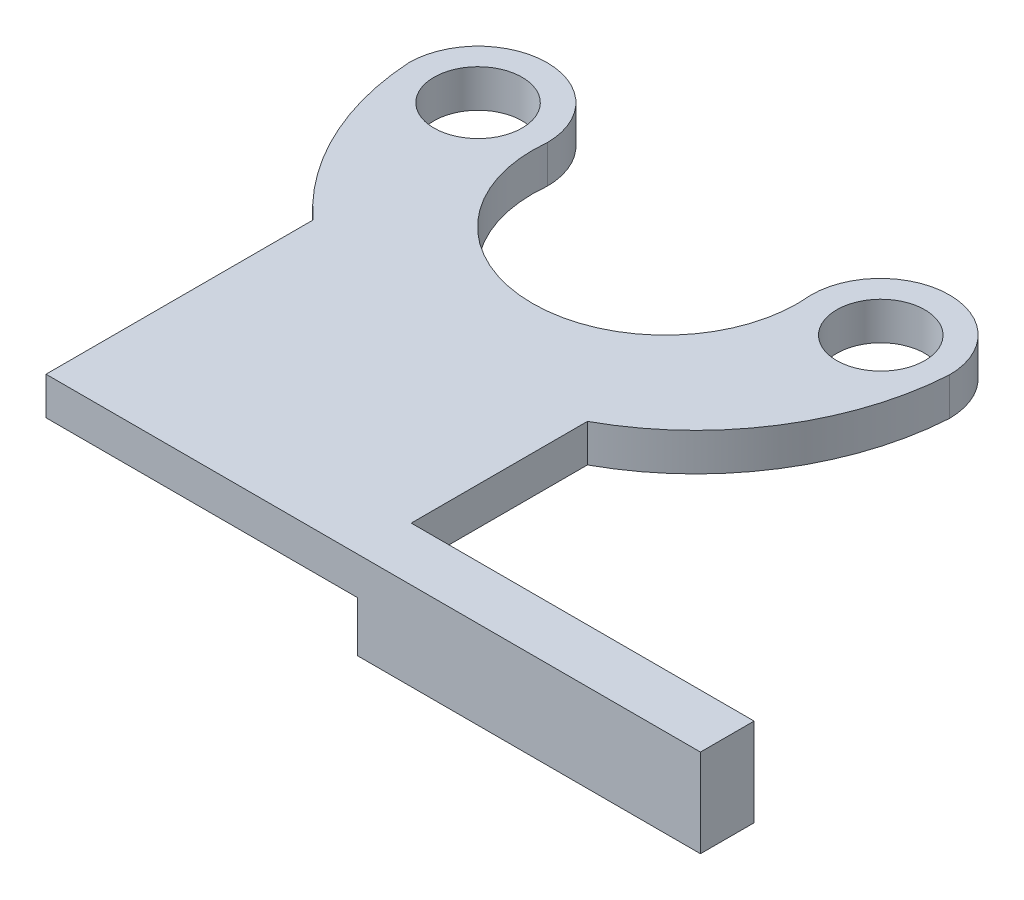
SolidWorks part; units mm, degrees
ref_plane "前视基准面" through (0, 0, 0) normal (0, 0, 1) x (1, 0, 0)
ref_plane "上视基准面" through (0, 0, 0) normal (0, 1, 0) x (1, 0, 0)
ref_plane "右视基准面" through (0, 0, 0) normal (1, 0, 0) x (0, 0, -1)
other "Configuration Table"
sketch "草图1" plane through (0, 0, 0) normal (0, 1, 0) x (1, 0, 0)
  line L0 (-7.2391, -7.3141) -> (-7.2391, -17.9247)
  line L1 (-7.2391, -17.9247) -> (18.7609, -17.9247)
  line L2 (18.7609, -15.7928) -> (18.7609, -17.9247)
  line L3 (18.7609, -15.7928) -> (5.1388, -15.7928)
  line L4 (5.1388, -15.7928) -> (5.1388, -8.7928)
  circle A1 centre (0, 0) radius 8 construction
  circle A2 centre (-8, 0) radius 1.75
  circle A3 centre (0, 8) radius 1.75 construction
  circle A4 centre (0, 0) radius 5 construction
  arc A5 (-5.25, 0) -> (-10.75, 0) centre (-8, 0) ccw
  circle A6 centre (8, 0) radius 1.75
  circle A7 centre (0, -8) radius 1.75 construction
  arc A8 (10.7305, 0) -> (5.2305, 0) centre (7.9805, 0) ccw
  arc A9 (-5.25, 0) -> (5.2305, 0) centre (-0.0097, -0.5576) ccw
  arc A10 (10.7305, 0) -> (5.1388, -8.7928) centre (-0.0097, 0.6558) cw
  arc A11 (-7.2391, -7.3141) -> (-10.75, 0) centre (-0.0097, 0.6558) cw
  point P9 (0, 0)
  point P18 (-0.0097, 0)
  dimension "D4" = 10
  dimension "D5" = 5.5
  dimension "D6" = 2
  dimension "D7" = 2.1319
  dimension "D8" = 7
  dimension "D10" = 26
  dimension "D3" = 4
extrude "凸台-拉伸1" add sketch "草图1" along normal blind 1.5
sketch "草图2" plane through (0, 1.5, 0) normal (0, 1, 0) x (1, 0, 0)
  line L1 (5.1388, -15.7928) -> (18.7609, -15.7928)
  line L2 (5.1388, -15.7928) -> (5.1388, -17.9247)
  line L3 (5.1388, -17.9247) -> (18.7609, -17.9247)
  line L4 (18.7609, -15.7928) -> (18.7609, -17.9247)
extrude "凸台-拉伸2" add sketch "草图2" against normal blind 3.5
